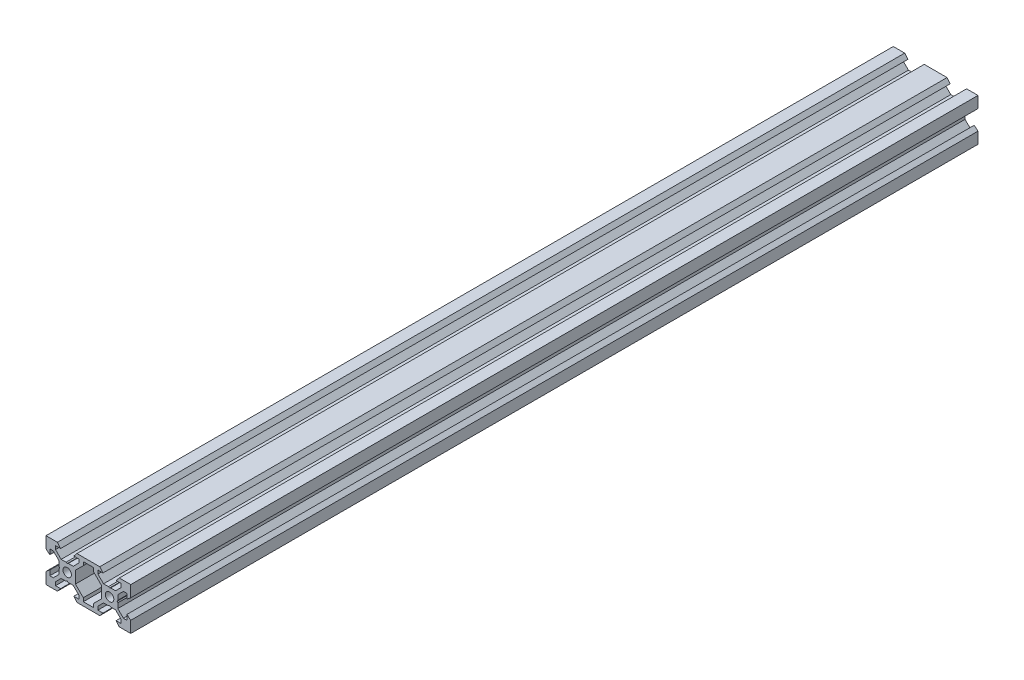
SolidWorks part; units mm, degrees
ref_plane "Front Plane" through (0, 0, 0) normal (0, 0, 1) x (1, 0, 0)
ref_plane "Top Plane" through (0, 0, 0) normal (0, 1, 0) x (1, 0, 0)
ref_plane "Right Plane" through (0, 0, 0) normal (1, 0, 0) x (0, 0, -1)
sketch "Sketch1" plane through (0, 0, 0) normal (0, 0, 1) x (1, 0, 0)
  line L0 (-5.3896, 10) -> (5.3896, 10)
  line L1 (0, 10) -> (0, 4.6104) construction
  line L2 (-6.1, -2.8393) -> (-2.3769, -6.5562)
  line L3 (5.3896, -10) -> (-5.3896, -10) construction
  line L5 (-6.1, 2.8393) -> (-6.1, -2.8393)
  line L6 (-4.5, 8.2) -> (-4.5, 6.5562)
  line L7 (2.3832, 6.5562) -> (2.3832, 8.2)
  line L9 (-6.1, 2.8393) -> (-2.3832, 6.5562)
  line L10 (-4.5, 6.5562) -> (-7.1607, 3.9)
  line L11 (-2.3832, 6.5562) -> (-2.3832, 8.2)
  line L12 (-5.3896, 10) -> (-6.9, 8.2)
  line L13 (6.1, 2.8393) -> (2.3832, 6.5562)
  line L14 (-6.9, 8.2) -> (-4.5, 8.2)
  line L15 (-16.5562, 5.5) -> (-18.2, 5.5)
  line L16 (0, 0) -> (6.1, 0) construction
  line L17 (-6.9, -8.2) -> (-4.5, -8.2)
  line L18 (-2.3769, -6.5562) -> (-2.3769, -8.2)
  line L19 (-5.3896, -10) -> (-6.9, -8.2)
  line L20 (2.3769, -6.5562) -> (2.3769, -8.2)
  line L21 (-9.4804, -3.9002) -> (-10, -3.6002)
  line L22 (-9.4804, 3.8998) -> (-10, 3.5998)
  line L23 (6.1, -2.8393) -> (2.3769, -6.5562)
  line L24 (-2.3769, -8.2) -> (2.3769, -8.2)
  line L25 (-2.3832, 8.2) -> (2.3832, 8.2)
  line L26 (-9.4804, 3.8998) -> (-7.1607, 3.9)
  line L27 (-5.3896, -10) -> (5.3896, -10)
  line L28 (-9.4804, -3.9002) -> (-7.1604, -3.9002)
  line L29 (-4.5, -6.5562) -> (-7.1607, -3.9)
  line L30 (-20, 10) -> (20, 10) construction
  line L32 (6.1, 2.8393) -> (6.1, -2.8393)
  line L33 (-4.5, -8.2) -> (-4.5, -6.5562)
  line L34 (-16.5562, -5.5) -> (-18.2, -5.5)
  line L36 (-10, 0) -> (-10, 8.2) construction
  line L37 (-20, -10) -> (-14.6104, -10) construction
  line L38 (-20, -10) -> (-20, -4.6104) construction
  line L39 (-20, 10) -> (-20, 4.6104) construction
  line L40 (-20, 10) -> (-14.6104, 10) construction
  line L41 (-20, -10) -> (-20, -4.6104)
  line L42 (-15.5, -8.2) -> (-15.5, -6.5562)
  line L43 (-20, -10) -> (-14.6104, -10)
  line L44 (7.1519, 3.8998) -> (9.4804, 3.8998)
  line L45 (-16.5562, -5.5) -> (-13.9, -2.8393)
  line L46 (-15.5, -6.5562) -> (-12.8393, -3.9)
  line L47 (-12.8393, -3.9) -> (-10.5196, -3.9002)
  line L48 (-13.9, -2.8393) -> (-13.9, -0.5196)
  line L49 (-12.8393, 3.9) -> (-10.5196, 3.8998)
  line L50 (-13.9, 0.5196) -> (-13.9, 2.8393)
  line L51 (-13.9, 0.5196) -> (-13.6, 0)
  line L52 (-13.6, 0) -> (-13.9, -0.5196)
  line L53 (-10.5196, 3.8998) -> (-10, 3.5998)
  line L54 (-10.5196, -3.9002) -> (-10, -3.6002)
  line L55 (-20, -4.6104) -> (-18.2, -3.1)
  line L56 (-14.6104, -10) -> (-13.1, -8.2)
  line L57 (-18.2, -3.1) -> (-18.2, -5.5)
  line L58 (-13.1, -8.2) -> (-15.5, -8.2)
  line L59 (-20, -10) -> (20, -10) construction
  line L60 (-20, -10) -> (-20, 10) construction
  line L61 (-13.1, 8.2) -> (-15.5, 8.2)
  line L62 (-18.2, 3.1) -> (-18.2, 5.5)
  line L63 (-14.6104, 10) -> (-13.1, 8.2)
  line L64 (-20, 4.6104) -> (-18.2, 3.1)
  line L65 (-15.5, 6.5562) -> (-12.8393, 3.9)
  line L66 (-16.5562, 5.5) -> (-13.9, 2.8393)
  line L67 (-20, 10) -> (-20, 4.6104)
  line L68 (-20, 10) -> (-14.6104, 10)
  line L69 (-15.5, 8.2) -> (-15.5, 6.5562)
  line L70 (4.5, 6.5562) -> (7.1519, 3.8998)
  line L71 (15.5, 6.5562) -> (12.8481, 3.8998)
  line L72 (0, -10) -> (0, 10) construction
  line L73 (-20, -10) -> (0, 10) construction
  line L74 (10.5196, 3.8998) -> (12.8481, 3.8998)
  line L75 (12.8393, -3.9) -> (10.5192, -3.9)
  line L76 (20, -10) -> (0, 10) construction
  line L77 (20, -10) -> (20, 10) construction
  line L78 (20, 10) -> (14.6104, 10) construction
  line L79 (20, 10) -> (20, 4.6104) construction
  line L80 (20, -10) -> (20, -4.6104) construction
  line L81 (20, -10) -> (14.6104, -10) construction
  line L82 (10, 0) -> (10, 8.2) construction
  line L83 (20, 10) -> (20, 4.6104)
  line L84 (15.5, 8.2) -> (15.5, 6.5562)
  line L85 (20, 10) -> (14.6104, 10)
  line L87 (16.5562, 5.5) -> (13.9, 2.8393)
  line L89 (20, 4.6104) -> (18.2, 3.1)
  line L90 (14.6104, 10) -> (13.1, 8.2)
  line L91 (18.2, 3.1) -> (18.2, 5.5)
  line L92 (13.1, 8.2) -> (15.5, 8.2)
  line L93 (13.1, -8.2) -> (15.5, -8.2)
  line L94 (18.2, -3.1) -> (18.2, -5.5)
  line L95 (14.6104, -10) -> (13.1, -8.2)
  line L96 (20, -4.6104) -> (18.2, -3.1)
  line L97 (10.5196, -3.9002) -> (10, -3.6002)
  line L98 (10.5196, 3.8998) -> (10, 3.5998)
  line L99 (13.6, 0) -> (13.9, -0.5196)
  line L100 (13.9, 0.5196) -> (13.6, 0)
  line L101 (13.9, 0.5196) -> (13.9, 2.8393)
  line L102 (9.4808, -3.9) -> (7.1607, -3.9)
  line L103 (13.9, -2.8393) -> (13.9, -0.5196)
  line L105 (15.5, -6.5562) -> (12.8393, -3.9)
  line L106 (16.5562, -5.5) -> (13.9, -2.8393)
  line L107 (20, -10) -> (20, -4.6104)
  line L108 (20, -10) -> (14.6104, -10)
  line L109 (15.5, -8.2) -> (15.5, -6.5562)
  line L111 (16.5562, -5.5) -> (18.2, -5.5)
  line L112 (4.5, -8.2) -> (4.5, -6.5562)
  line L114 (4.5, -6.5562) -> (7.1607, -3.9)
  line L121 (9.4804, 3.8998) -> (10, 3.5998)
  line L122 (9.4804, -3.9002) -> (10, -3.6002)
  line L124 (5.3896, -10) -> (6.9, -8.2)
  line L126 (6.9, -8.2) -> (4.5, -8.2)
  line L128 (16.5562, 5.5) -> (18.2, 5.5)
  line L129 (6.9, 8.2) -> (4.5, 8.2)
  line L131 (5.3896, 10) -> (6.9, 8.2)
  line L135 (4.5, 8.2) -> (4.5, 6.5562)
  circle A0 centre (-10, 0) radius 2
  circle A1 centre (10, 0) radius 2
  dimension "D14" = 4
  dimension "D1" = 20
  dimension "D2" = 5.3896
  dimension "D3" = 1.8
  dimension "D4" = 1.5104
  dimension "D5" = 4.5
  dimension "D6" = 5.5
  dimension "D7" = 120
  dimension "D8" = 0.3
  dimension "D9" = 2.3197
  dimension "D10" = 7.8
  dimension "D11" = 20
  dimension "D12" = 1.5
  dimension "D13" = 2.6607
  dimension "D15" = 50
  dimension "D16" = 1.5
  dimension "D17" = 1.8
  dimension "D18" = 16.4
  dimension "D19" = 2.3832
  dimension "D20" = 45
extrude "Boss-Extrude1" add sketch "Sketch1" along normal blind 400
